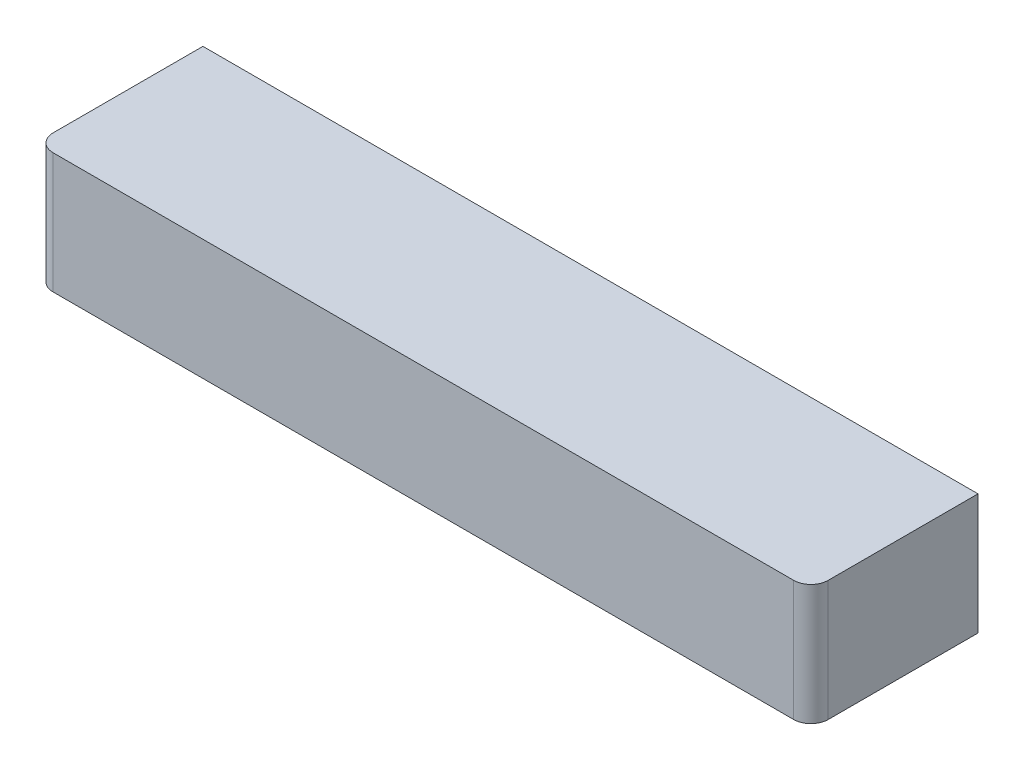
SolidWorks part; units mm, degrees
ref_plane "Front Plane" through (0, 0, 0) normal (0, 0, 1) x (1, 0, 0)
ref_plane "Top Plane" through (0, 0, 0) normal (0, 1, 0) x (1, 0, 0)
ref_plane "Right Plane" through (0, 0, 0) normal (1, 0, 0) x (0, 0, -1)
sketch "Sketch1" plane through (0, 0, 0) normal (0, 1, 0) x (1, 0, 0)
  line L1 (-255.3123, -84.3644) -> (194.6877, -84.3644)
  line L2 (-255.3123, -84.3644) -> (-255.3123, 12.6356)
  line L3 (-255.3123, 12.6356) -> (194.6877, 12.6356)
  line L4 (194.6877, -84.3644) -> (194.6877, 12.6356)
  dimension "D1" = 450
  dimension "D2" = 97
extrude "Boss-Extrude1" add sketch "Sketch1" along normal blind 70
fillet "Fillet1" radius 10 2 edges at (-255.3123, 35, 84.3644) (194.6877, 35, 84.3644)
sketch "Sketch2" plane through (0, 0, 0) normal (0, -1, 0) x (-1, 0, 0)
  line L0 (245.3123, -84.3644) -> (-184.6877, -84.3644) construction
  line L1 (255.3123, 12.6356) -> (255.3123, -74.3644) construction
  line L2 (-194.6877, -74.3644) -> (-194.6877, 12.6356) construction
  circle A0 centre (-184.6877, -44.3644) radius 1.5
  circle A1 centre (245.3123, -44.3644) radius 1.5
  dimension "D1" = 40
  dimension "D2" = 40
  dimension "D3" = 10
  dimension "D4" = 10
extrude "Cut-Extrude1" cut sketch "Sketch2" against normal blind 20
